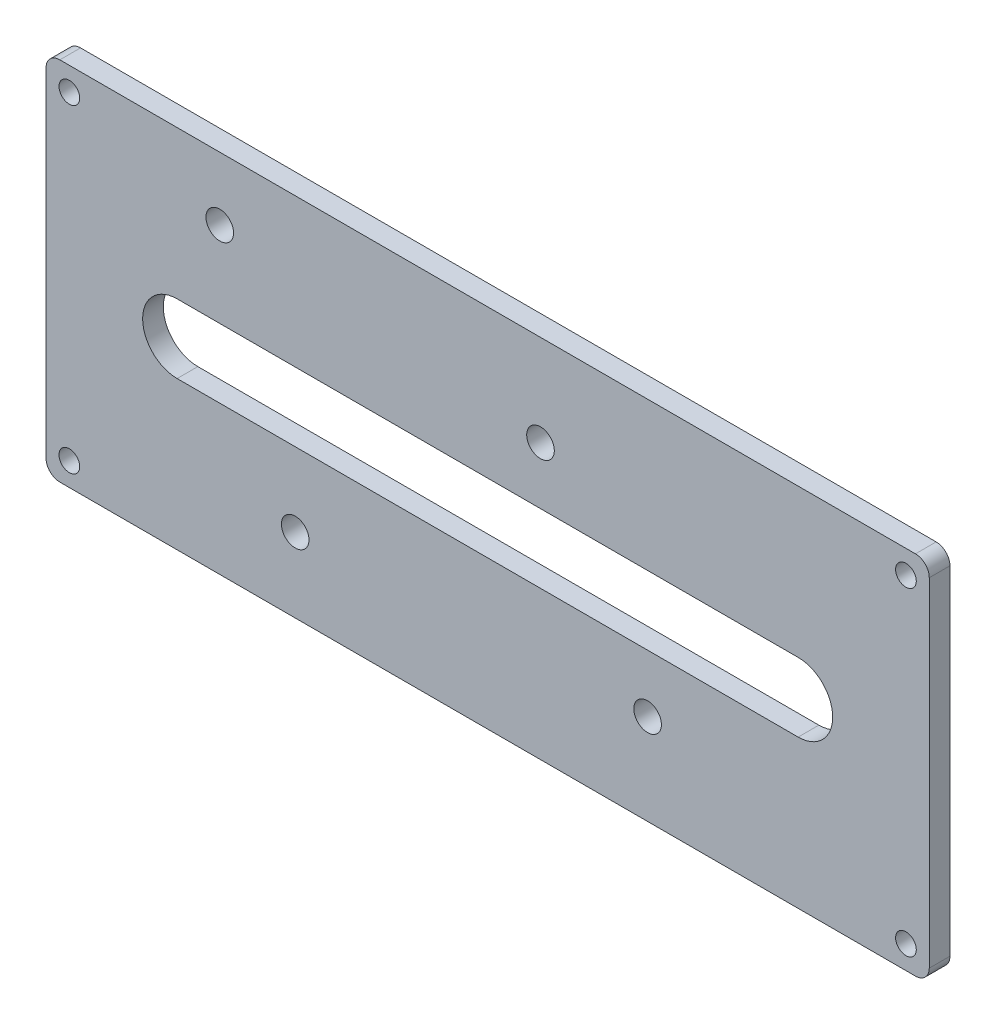
SolidWorks part; units mm, degrees
ref_plane "Plan de face" through (0, 0, 0) normal (0, 0, 1) x (1, 0, 0)
ref_plane "Plan de dessus" through (0, 0, 0) normal (0, 1, 0) x (1, 0, 0)
ref_plane "Plan de droite" through (0, 0, 0) normal (1, 0, 0) x (0, 0, -1)
sketch "Esquisse1" plane through (0, 0, 0) normal (0, 0, 1) x (1, 0, 0)
  line L0 (-64, 26.5) -> (64, -26.5) construction
  line L1 (-64, 26.5) -> (64, 26.5)
  line L2 (-64, 26.5) -> (-64, -26.5)
  line L3 (-64, -26.5) -> (64, -26.5)
  line L4 (64, 26.5) -> (64, -26.5)
  dimension "D1" = 128
  dimension "D2" = 53
extrude "Boss.-Extru.1" add sketch "Esquisse1" along normal blind 3
sketch "Esquisse2" plane through (0, 0, 3) normal (0, 0, 1) x (1, 0, 0)
  line L1 (-64, 26.5) -> (-64, -26.5) construction
  line L2 (64, 26.5) -> (-64, 26.5) construction
  line L3 (-64, -26.5) -> (64, -26.5) construction
  circle A0 centre (-38.82, 17.35) radius 2
  circle A1 centre (7.66, 13.27) radius 2
  circle A2 centre (-27.89, -15.71) radius 2
  circle A3 centre (23.18, -13.35) radius 2
  dimension "D1" = 4
  dimension "D2" = 4
  dimension "D3" = 4
  dimension "D4" = 4
  dimension "D5" = 25.18
  dimension "D6" = 9.15
  dimension "D7" = 46.48
  dimension "D8" = 13.23
  dimension "D9" = 36.11
  dimension "D10" = 10.79
  dimension "D11" = 51.07
  dimension "D12" = 13.15
extrude "Enlèv. mat.-Extru.1" cut sketch "Esquisse2" against normal blind 3
sketch "Esquisse3" plane through (0, 0, 3) normal (0, 0, 1) x (1, 0, 0)
  line L0 (-45, 5) -> (45, -5) construction
  line L1 (-45, 5) -> (45, 5)
  line L3 (-45, -5) -> (45, -5)
  arc A0 (-45, 5) -> (-45, -5) centre (-45, 0) ccw
  arc A1 (45, 5) -> (45, -5) centre (45, 0) cw
  dimension "D2" = 5
  dimension "D3" = 5
  dimension "D1" = 10
  dimension "D4" = 90
  dimension "D5" = 10
extrude "Enlèv. mat.-Extru.2" cut sketch "Esquisse3" against normal blind 3
sketch "Esquisse5" plane through (0, 0, 3) normal (0, 0, 1) x (1, 0, 0)
  line L0 (-64, 26.5) -> (-64, -26.5) construction
  line L1 (64, 26.5) -> (-64, 26.5) construction
  line L2 (64, -26.5) -> (64, 26.5) construction
  line L3 (-64, -26.5) -> (64, -26.5) construction
  circle A0 centre (-60.62, 23.12) radius 1.5
  circle A1 centre (60.62, 23.12) radius 1.5
  circle A2 centre (-60.62, -23.12) radius 1.5
  circle A3 centre (60.62, -23.12) radius 1.5
  dimension "D9" = 3
  dimension "D10" = 3
  dimension "D11" = 3
  dimension "D12" = 3
  dimension "D1" = 3.38
  dimension "D2" = 3.38
  dimension "D3" = 3.38
  dimension "D4" = 3.38
  dimension "D5" = 3.38
  dimension "D6" = 3.38
  dimension "D7" = 3.38
  dimension "D8" = 3.38
extrude "Enlèv. mat.-Extru.3" cut sketch "Esquisse5" against normal blind 3
fillet "Congé1" radius 2 4 edges at (64, -26.5, 1.5) (-64, -26.5, 1.5) (64, 26.5, 1.5) (-64, 26.5, 1.5)
